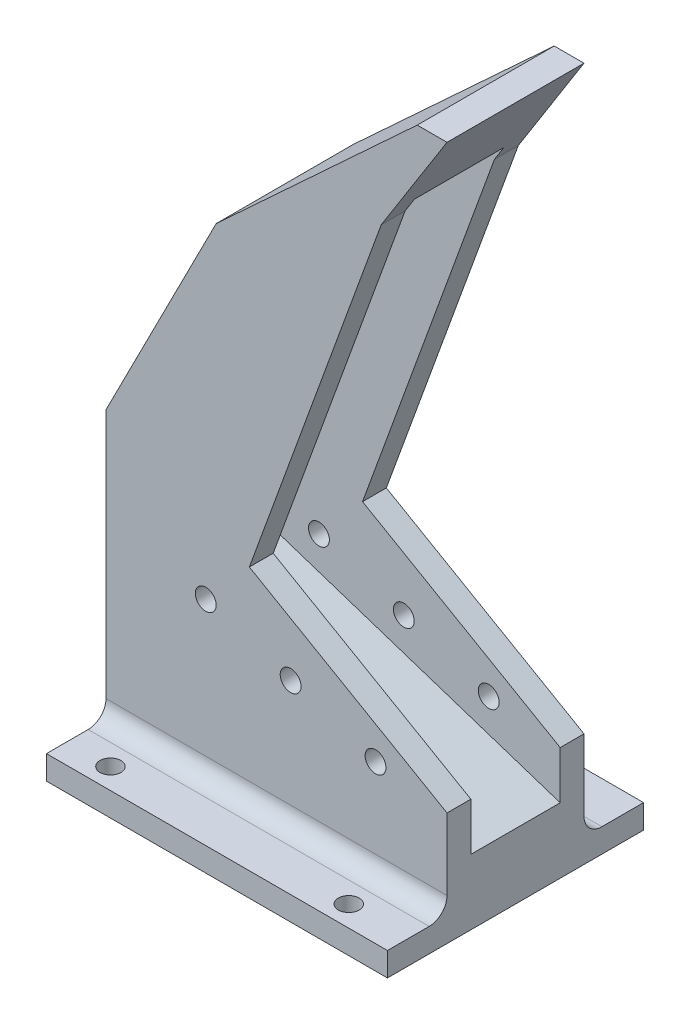
SolidWorks part; units mm, degrees
ref_plane "Front Plane" through (0, 0, 0) normal (0, 0, 1) x (1, 0, 0)
ref_plane "Top Plane" through (0, 0, 0) normal (0, 1, 0) x (1, 0, 0)
ref_plane "Right Plane" through (0, 0, 0) normal (1, 0, 0) x (0, 0, -1)
sketch "Sketch1" plane through (0, 0, 0) normal (0, 0, 1) x (1, 0, 0)
  line L0 (0, 0) -> (57.2501, 0)
  line L1 (57.2501, 0) -> (57.2501, 15)
  line L2 (57.2501, 15) -> (24.066, 34.1588)
  line L3 (24.066, 34.1588) -> (46.2104, 95)
  line L4 (46.2104, 95) -> (57.2501, 112.5)
  line L5 (57.2501, 112.5) -> (52.2501, 112.5)
  line L6 (18.5033, 81.3148) -> (0, 45)
  line L7 (0, 45) -> (0, 0)
  line L8 (57.2501, 112.5) -> (57.2501, 7.5) construction
  line L9 (57.2501, 7.5) -> (5, 24.6736) construction
  line L10 (5, 24.6736) -> (5, 29.6736) construction
  line L11 (5, 29.6736) -> (57.2501, 112.5) construction
  line L12 (52.2501, 112.5) -> (18.5033, 81.3148)
  line L13 (52.2501, 112.5) -> (34.393, 112.5) construction
  line L14 (34.393, 112.5) -> (18.5033, 81.3148) construction
  dimension "D2" = 5
  dimension "D3" = 30
  dimension "D4" = 70
  dimension "D5" = 63
  dimension "D6" = 45
  dimension "D7" = 105
  dimension "D8" = 97.93
  dimension "D9" = 5
  dimension "D10" = 55
  dimension "D11" = 35
  dimension "D12" = 15
  dimension "D13" = 80
  dimension "D14" = 5
extrude "Boss-Extrude1" add sketch "Sketch1" along normal mid plane 23 contours L5 L12 L6 L7 L0 L1 L2 L3 L4
sketch "Sketch2" plane through (0, 0, 0) normal (0, 0, 1) x (1, 0, 0)
  line L0 (21.7429, 78.8621) -> (4, 44.0397)
  line L1 (4, 44.0397) -> (4, 24.4759)
  line L2 (5, 29.6736) -> (57.2501, 112.5) construction
  line L5 (47.7875, 97.5) -> (57.2501, 112.5)
  line L11 (57.2501, 0) -> (57.2501, 15) construction
  line L12 (4, 24.4759) -> (57.2501, 6.9737)
  line L14 (47.7875, 97.5) -> (47.7875, 102.9298)
  line L18 (57.2501, 112.5) -> (52.2501, 112.5) construction
  line L19 (46.2104, 95) -> (57.2501, 112.5) construction
  line L21 (0, 45) -> (0, 0) construction
  line L22 (0, 0) -> (57.2501, 0) construction
  line L23 (0, 45) -> (0, 0)
  line L24 (0, 0) -> (57.2501, 0)
  line L27 (57.2501, 6.9737) -> (57.2501, 0)
  line L31 (57.2501, 7.5) -> (5, 24.6736) construction
  line L33 (21.7429, 78.8621) -> (47.7875, 102.9298)
  line L34 (52.2501, 112.5) -> (18.5033, 81.3148) construction
  line L35 (18.5033, 81.3148) -> (0, 45) construction
  line L36 (52.2501, 112.5) -> (18.5033, 81.3148)
  line L37 (18.5033, 81.3148) -> (0, 45)
  line L38 (57.2501, 112.5) -> (52.2501, 112.5)
  dimension "D1" = 4
  dimension "D2" = 15
  dimension "D3" = 4
  dimension "D4" = 4
  dimension "D5" = 0.5
extrude "Cut-Extrude2" cut sketch "Sketch2" against normal mid plane 15 flip side to cut
sketch "Sketch4" plane through (0, 0, 11.5) normal (0, 0, 1) x (1, 0, 0)
  line L1 (5, 29.6736) -> (57.2501, 12.5) construction
  line L2 (57.2501, 0) -> (57.2501, 15) construction
  line L3 (57.2501, 7.5) -> (5, 24.6736) construction
  circle A0 centre (45.2501, 16.4442) radius 1.75
  circle A1 centre (31, 21.1279) radius 1.75
  circle A2 centre (16.75, 25.8116) radius 1.75
  dimension "D4" = 3.5
  dimension "D1" = 12
  dimension "D2" = 15
  dimension "D3" = 15
extrude "Cut-Extrude3" cut sketch "Sketch4" against normal through all both and the other way through all
sketch "Sketch5" plane through (0, 0, 0) normal (0, -1, 0) x (1, 0, 0)
  line L0 (0, 11.5) -> (57.2501, -11.5) construction
  line L1 (0, 11.5) -> (57.2501, 11.5) construction
  line L2 (0, 21.5) -> (57.2501, 21.5)
  line L3 (0, 21.5) -> (0, -21.5)
  line L4 (0, -21.5) -> (57.2501, -21.5)
  line L5 (57.2501, 21.5) -> (57.2501, -21.5)
  line L6 (0, 21.5) -> (57.2501, -21.5) construction
  line L7 (0, -21.5) -> (57.2501, 21.5) construction
  line L8 (57.2501, 11.5) -> (57.2501, -11.5) construction
  point P4 (28.625, 0)
  dimension "D1" = 10
extrude "Boss-Extrude2" add sketch "Sketch5" along normal blind 4
sketch "Sketch6" plane through (0, 0, 0) normal (0, 1, 0) x (1, 0, 0)
  line L0 (0, 18) -> (57.2501, 18) construction
  line L3 (0, 11.5) -> (0, 21.5) construction
  line L4 (57.2501, 21.5) -> (57.2501, 11.5) construction
  circle A1 centre (7.2501, 18) radius 1.75
  circle A2 centre (47.2501, 18) radius 1.75
  dimension "D1" = 40
  dimension "D2" = 3.5
  dimension "D3" = 10
  dimension "D4" = 18
extrude "Cut-Extrude4" cut sketch "Sketch6" against normal through all both and the other way through all
mirror "Mirror5" about plane through (0, 0, 0) normal (0, 0, 1) of "Cut-Extrude4"
fillet "Fillet1" radius 3 2 edges at (28.625, 0, -11.5) (28.625, 0, 11.5)
equation "\"D3@Sketch4\"=\"D2@Sketch4\""
